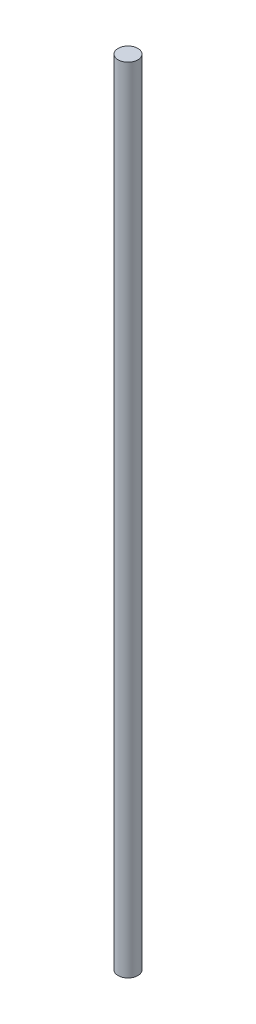
SolidWorks part; units mm, degrees
ref_plane "Спереди" through (0, 0, 0) normal (0, 0, 1) x (1, 0, 0)
ref_plane "Сверху" through (0, 0, 0) normal (0, 1, 0) x (1, 0, 0)
ref_plane "Справа" through (0, 0, 0) normal (1, 0, 0) x (0, 0, -1)
sketch "Эскиз1" plane through (0, 0, 0) normal (0, 1, 0) x (1, 0, 0)
  circle A0 centre (0, 0) radius 5
  dimension "D1" = 10
extrude "Бобышка-Вытянуть1" add sketch "Эскиз1" along normal blind 400
